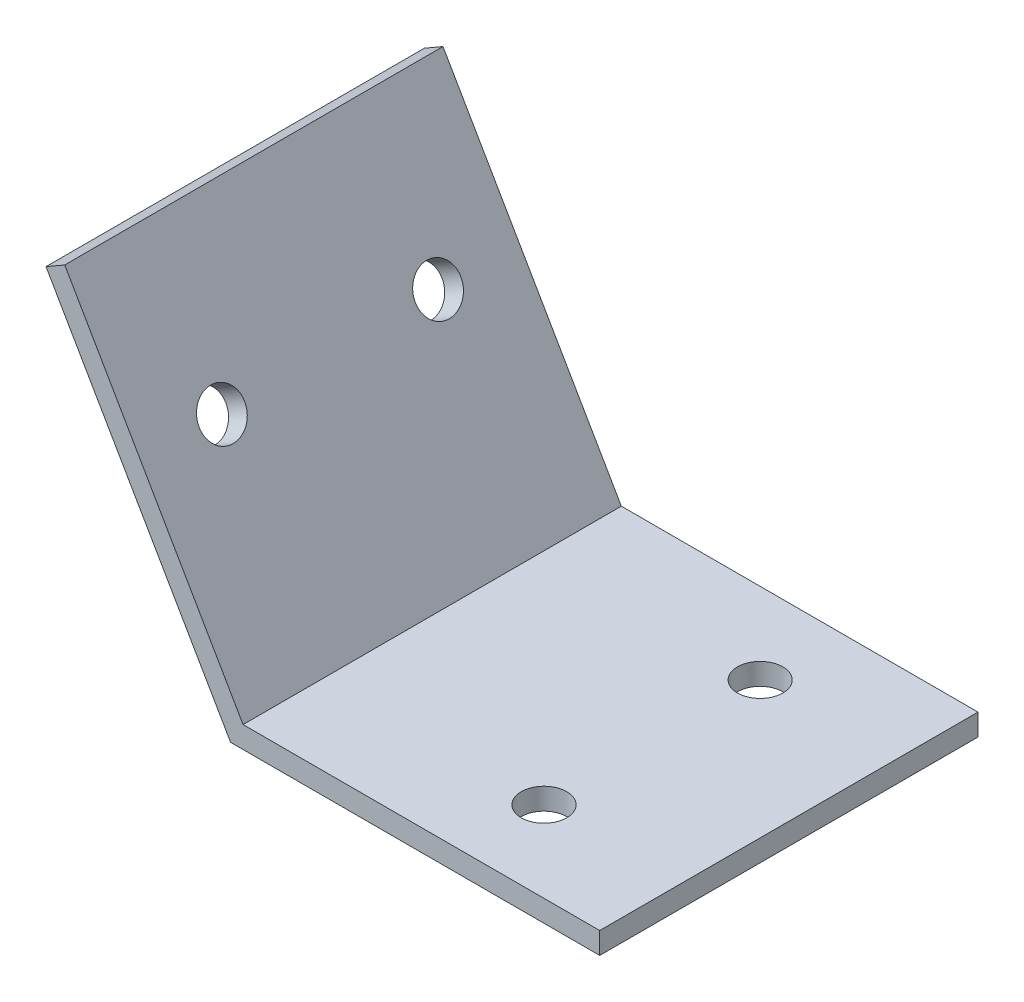
SolidWorks part; units mm, degrees
ref_plane "前视基准面" through (0, 0, 0) normal (0, 0, 1) x (1, 0, 0)
ref_plane "上视基准面" through (0, 0, 0) normal (0, 1, 0) x (1, 0, 0)
ref_plane "右视基准面" through (0, 0, 0) normal (1, 0, 0) x (0, 0, -1)
other "Configuration Table"
sketch "草图1" plane through (0, 0, 0) normal (0, 0, 1) x (1, 0, 0)
  line L0 (0, 0) -> (34.1547, 0)
  line L1 (34.1547, 0) -> (34.1547, 2)
  line L2 (34.1547, 2) -> (1.1547, 2)
  line L3 (1.1547, 2) -> (-15.3453, 30.5788)
  line L4 (-15.3453, 30.5788) -> (-17.0774, 29.5788)
  line L5 (-17.0774, 29.5788) -> (0, 0)
  dimension "D1" = 120
  dimension "D2" = 120
  dimension "D3" = 33
  dimension "D4" = 33
  dimension "D5" = 2
  dimension "D6" = 2
extrude "凸台-拉伸3" add sketch "草图1" along normal blind 35
sketch "草图3" plane through (0, 0, 0) normal (0, -1, 0) x (1, 0, 0)
  line L0 (0, 17.5) -> (34.1547, 17.5) construction
  line L1 (0, 35) -> (0, 0) construction
  line L2 (34.1547, 35) -> (34.1547, 0) construction
  circle A0 centre (21.5, 27.5) radius 2.1
  circle A1 centre (21.5, 7.5) radius 2.1
  dimension "D1" = 10
  dimension "D2" = 21.5
extrude "切除-拉伸1" cut sketch "草图3" against normal through all
sketch "草图4" plane through (0, 0, 0) normal (-0.866, -0.5, 0) x (0, 0, 1)
  line L0 (17.5, 0) -> (17.5, 34.1547) construction
  line L1 (35, 0) -> (0, 0) construction
  line L2 (35, 34.1547) -> (0, 34.1547) construction
  circle A0 centre (27.5, 20.07) radius 2.1
  circle A1 centre (7.5, 20.07) radius 2.1
  dimension "D1" = 10
  dimension "D2" = 20.07
extrude "切除-拉伸2" cut sketch "草图4" against normal through all
